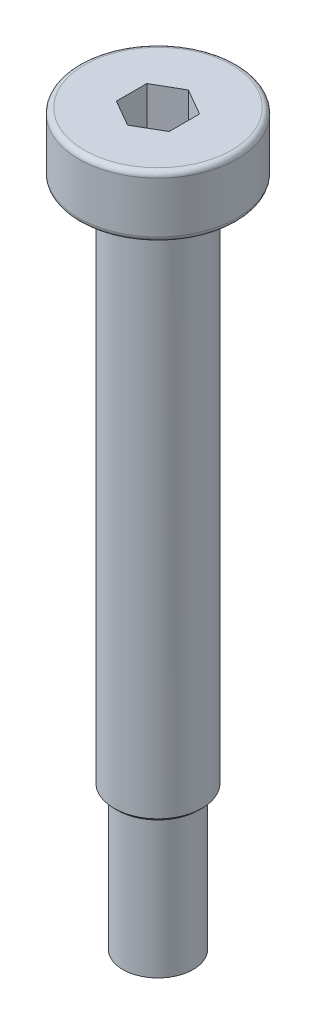
SolidWorks part; units mm, degrees
ref_plane "前视基准面" through (0, 0, 0) normal (0, 0, 1) x (1, 0, 0)
ref_plane "上视基准面" through (0, 0, 0) normal (0, 1, 0) x (1, 0, 0)
ref_plane "右视基准面" through (0, 0, 0) normal (1, 0, 0) x (0, 0, -1)
sketch "草图1" plane through (0, 0, 0) normal (0, 0, 1) x (1, 0, 0)
  line L0 (0, 3.5) -> (0, -15.6048) construction
  line L1 (0, 3.5) -> (-4.5, 3.5)
  line L2 (-4.5, 3.5) -> (-4.5, 0)
  line L3 (-4.5, 0) -> (-2.5, 0)
  line L4 (-2.5, 0) -> (-2.5, -30)
  line L5 (-2.5, -30) -> (-2, -30)
  line L6 (-2, -30) -> (-2, -38)
  line L7 (-2, -38) -> (0, -38)
  line L8 (0, 3.5) -> (0, -38)
  point P0 (0, -26.25)
  point P5 (0, -11.9396)
  point P12 (0, 0)
  point P13 (0, 9.1221)
  point P15 (0, 0)
  point P16 (0, 0)
  point P17 (0, 0)
  point P18 (0, 0)
  point P19 (0, 0)
  dimension "D1" = 5
  dimension "D2" = 8
  dimension "D3" = 3.5
  dimension "D4" = 9
  dimension "D5" = 30
  dimension "D6" = 4
revolve "旋转1" add sketch "草图1" angle 360 about L0
cosmetic thread "装饰螺纹线1" parameters "D2"=3.242
fillet "圆角1" radius 0.3 2 edges at (-4.5, 0, 0) (-4.5, 3.5, 0)
sketch "草图2" plane through (0, 3.5, 0) normal (0, 1, 0) x (1, 0, 0)
  line L1 (0, 1.7321) -> (-1.5, 0.866)
  line L2 (-1.5, 0.866) -> (-1.5, -0.866)
  line L3 (-1.5, -0.866) -> (0, -1.7321)
  line L4 (0, -1.7321) -> (1.5, -0.866)
  line L5 (1.5, -0.866) -> (1.5, 0.866)
  line L6 (1.5, 0.866) -> (0, 1.7321)
  circle A0 centre (0, 0) radius 1.5 construction
  dimension "D1" = 3
extrude "切除-拉伸1" cut sketch "草图2" against normal blind 2.4
chamfer "倒角1" distance 0.2 angle 45 1 edges at (-2.5, -30, 0)
